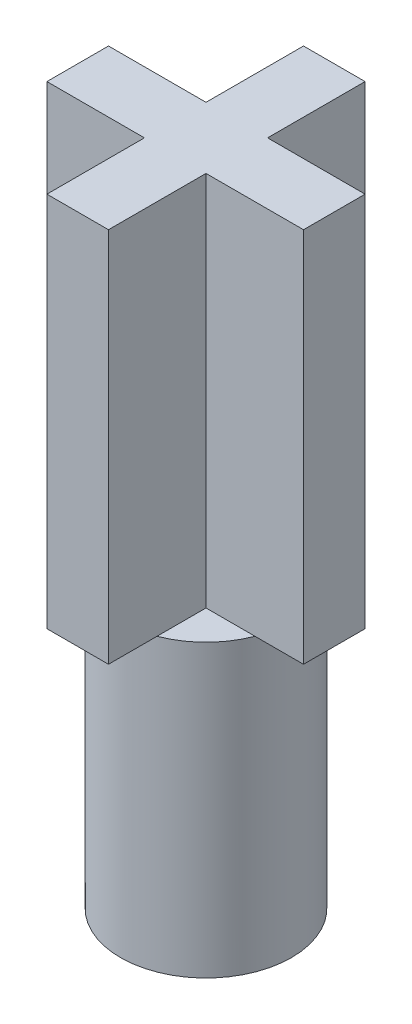
SolidWorks part; units mm, degrees
ref_plane "前视基准面" through (0, 0, 0) normal (0, 0, 1) x (1, 0, 0)
ref_plane "上视基准面" through (0, 0, 0) normal (0, 1, 0) x (1, 0, 0)
ref_plane "右视基准面" through (0, 0, 0) normal (1, 0, 0) x (0, 0, -1)
other "Configuration Table"
sketch "草图1" plane through (0, 0, 0) normal (0, 1, 0) x (1, 0, 0)
  line L0 (-4.329, 2.5019) -> (-4.329, -2.5019)
  line L2 (-1.4722, 2.2034) -> (-1.4722, -2.2034)
  arc A2 (-4.329, -2.5019) -> (-4.329, 2.5019) centre (0, 0) ccw
  arc A4 (-1.4722, -2.2034) -> (-1.4722, 2.2034) centre (0, 0) ccw
extrude "凸台-拉伸2" add sketch "草图1" along normal blind 15
sketch "草图2" plane through (0, 15, 0) normal (0, 1, 0) x (1, 0, 0)
  line L0 (-4.329, 2.5019) -> (-4.329, -2.5019)
  arc A0 (-4.329, -2.5019) -> (-4.329, 2.5019) centre (0, 0) ccw
extrude "凸台-拉伸3" add sketch "草图2" along normal blind 2
sketch "草图3" plane through (0, 17, 0) normal (0, 1, 0) x (1, 0, 0)
  line L0 (-7.5, 0) -> (-7.5, 1.8)
  line L1 (-7.5, 0) -> (-7.5, -1.8)
  line L2 (-7.5, -1.8) -> (-1.8, -1.8)
  line L3 (7.5, -1.8) -> (7.5, 1.8)
  line L4 (7.5, 1.8) -> (1.8, 1.8)
  line L5 (0, 7.5) -> (-1.8, 7.5)
  line L6 (0, 7.5) -> (1.8, 7.5)
  line L7 (1.8, 7.5) -> (1.8, 1.8)
  line L8 (1.8, -7.5) -> (-1.8, -7.5)
  line L9 (-1.8, -7.5) -> (-1.8, -1.8)
  line L10 (-1.8, 1.8) -> (-7.5, 1.8)
  line L11 (-1.8, 1.8) -> (-1.8, 7.5)
  line L12 (1.8, -1.8) -> (7.5, -1.8)
  line L13 (1.8, -1.8) -> (1.8, -7.5)
  point P0 (0, 7.5)
  point P1 (0, -7.5)
  point P2 (-7.5, 0)
  point P3 (7.5, 0)
  dimension "D1" = 7.5
  dimension "D2" = 7.5
  dimension "D3" = 7.5
  dimension "D4" = 7.5
extrude "凸台-拉伸4" add sketch "草图3" along normal blind 22
